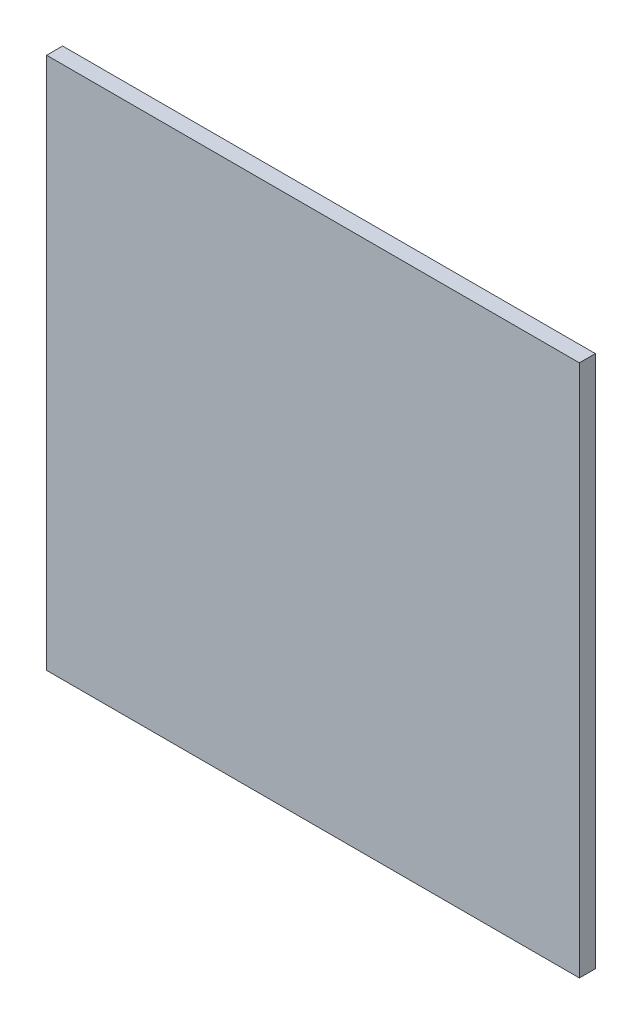
SolidWorks part; units mm, degrees
ref_plane "Front Plane" through (0, 0, 0) normal (0, 0, 1) x (1, 0, 0)
ref_plane "Top Plane" through (0, 0, 0) normal (0, 1, 0) x (1, 0, 0)
ref_plane "Right Plane" through (0, 0, 0) normal (1, 0, 0) x (0, 0, -1)
sketch "Sketch1" plane through (0, 0, 0) normal (0, 0, 1) x (1, 0, 0)
  line L1 (-50, -50) -> (50, -50)
  line L2 (-50, -50) -> (-50, 50)
  line L3 (-50, 50) -> (50, 50)
  line L4 (50, -50) -> (50, 50)
  line L5 (-50, -50) -> (50, 50) construction
  line L6 (-50, 50) -> (50, -50) construction
  point P0 (0, 0)
extrude "Boss-Extrude1" add sketch "Sketch1" along normal blind 3
sketch "Sketch2" plane through (0, 0, 3) normal (0, 0, 1) x (1, 0, 0)
  line L0 (-7.55, -1.32) -> (-5.64, -10.7)
  line L1 (-5.64, -10.7) -> (-5.35, -13.34)
  line L2 (-5.35, -13.34) -> (-5.5, -17.3)
  line L3 (-5.5, -17.3) -> (-6.08, -20.23)
  line L4 (-6.08, -20.23) -> (-6.82, -20.96)
  line L5 (-6.82, -20.96) -> (-9.6, -22.43)
  line L6 (-9.6, -22.43) -> (-9.93, -22.87)
  line L7 (-9.93, -22.87) -> (-9.89, -23.31)
  line L8 (-9.89, -23.31) -> (-9.45, -23.75)
  line L9 (-9.45, -23.75) -> (-5.94, -25.21)
  line L10 (-5.94, -25.21) -> (-5.06, -25.21)
  line L11 (-5.06, -25.21) -> (1.42, -21.87)
  line L12 (1.42, -21.87) -> (1.83, -21.4)
  line L13 (1.83, -21.4) -> (2.13, -13.49)
  line L14 (2.13, -13.49) -> (2.82, -7.33)
  line L15 (2.82, -7.33) -> (3.96, -5.67)
  line L16 (3.96, -5.67) -> (12.68, 0.29)
  line L17 (12.68, 0.29) -> (14.29, 1.76)
  line L18 (14.29, 1.76) -> (14, 2.64)
  line L19 (14, 2.64) -> (13.41, 3.08)
  line L20 (13.41, 3.08) -> (4.32, 6.89)
  line L21 (4.32, 6.89) -> (3, 8.21)
  line L22 (3, 8.21) -> (3, 8.79)
  line L23 (3, 8.79) -> (2.52, 9.28)
  line L24 (3.59, 7.33) -> (3.83, 7.3)
  line L25 (14.44, 5.13) -> (14.44, 6.74)
  line L26 (14.44, 6.74) -> (15.02, 9.82)
  line L27 (15.02, 9.82) -> (15.76, 12.17)
  line L28 (15.76, 12.17) -> (17.22, 15.24)
  line L29 (17.22, 15.24) -> (17.37, 16.42)
  line L30 (17.37, 16.42) -> (13.71, 22.43)
  line L31 (13.71, 22.43) -> (12.83, 23.01)
  line L32 (12.83, 23.01) -> (5.5, 23.45)
  line L33 (5.5, 23.45) -> (-0.07, 23.01)
  line L34 (0.37, 25.07) -> (-0.37, 27.56)
  line L35 (3.59, 28.29) -> (3.3, 28.88)
  line L36 (3.3, 28.88) -> (3.59, 32.69)
  line L37 (3.59, 32.69) -> (4.76, 37.52)
  line L38 (4.76, 37.52) -> (5.79, 38.99)
  line L39 (5.79, 38.99) -> (5.79, 40.75)
  line L40 (5.79, 40.75) -> (-0.22, 45)
  line L41 (-0.22, 45) -> (-1.54, 45)
  line L42 (-1.54, 45) -> (-7.21, 42.32)
  line L43 (-7.21, 42.32) -> (-8.14, 40.6)
  line L44 (-8.14, 40.6) -> (-9.45, 37.23)
  line L45 (-9.45, 37.23) -> (-9.75, 35.77)
  line L46 (-9.75, 35.77) -> (-10.09, 35.42)
  line L47 (-10.09, 35.42) -> (-12.02, 35.45)
  line L48 (-12.02, 35.45) -> (-12.68, 35.03)
  line L49 (-12.68, 35.03) -> (-19.13, 33.71)
  line L50 (-19.13, 33.71) -> (-20.3, 33.71)
  line L51 (-20.3, 33.71) -> (-27.92, 31.37)
  line L52 (-27.92, 31.37) -> (-30.27, 29.46)
  line L53 (-30.27, 29.46) -> (-33.35, 25.72)
  line L54 (-30.86, 25.8) -> (-30.23, 26.08)
  line L55 (-35.18, 22.72) -> (-36.28, 19.5)
  line L56 (-36.28, 19.5) -> (-37.01, 15.54)
  line L57 (-37.01, 15.54) -> (-37.52, 14.76)
  line L58 (-37.52, 14.76) -> (-40.97, 12.17)
  line L59 (-40.97, 12.17) -> (-42.43, 9.09)
  line L60 (-42.43, 9.09) -> (-42.43, 8.21)
  line L61 (-42.43, 8.21) -> (-41.12, 6.89)
  line L62 (-41.12, 6.89) -> (-40.82, 6.89)
  line L63 (-40.82, 6.89) -> (-40.84, 6.34)
  line L64 (-40.84, 6.34) -> (-40.38, 6.3)
  line L65 (-40.38, 6.3) -> (-39.36, 4.98)
  line L66 (-39.36, 4.98) -> (-38.59, 4.57)
  line L67 (-38.59, 4.57) -> (-37.89, 2.64)
  line L68 (-37.89, 2.64) -> (-38.04, 1.32)
  line L69 (-38.04, 1.32) -> (-39.21, -0.15)
  line L70 (-39.21, -0.15) -> (-39.47, -0.91)
  line L71 (-39.47, -0.91) -> (-40.53, -0.88)
  line L72 (-40.53, -0.88) -> (-42, 1.32)
  line L73 (-42, 1.32) -> (-42, 4.84)
  line L74 (-42, 4.84) -> (-39.5, 8.5)
  line L75 (-39.5, 8.5) -> (-38.33, 8.65)
  line L76 (-38.33, 8.65) -> (-36.64, 8.14)
  line L77 (-33.86, 11.8) -> (-32.91, 12.83)
  line L78 (-32.91, 12.83) -> (-31.88, 13.19)
  line L79 (-31.88, 13.19) -> (-24.7, 12.46)
  line L80 (-24.7, 12.46) -> (-24.32, 12.23)
  line L81 (-23.75, 15.39) -> (-24.26, 14.22)
  line L82 (-24.26, 14.22) -> (-24.41, 12.75)
  line L83 (-24.41, 12.75) -> (-23.82, 10.85)
  line L84 (-23.82, 10.85) -> (-22.06, 7.77)
  line L85 (-22.06, 7.77) -> (-22.06, 6.89)
  line L86 (-22.06, 6.89) -> (-22.37, 6.45)
  line L87 (-24.48, 0.07) -> (-19.57, -3.08)
  line L88 (-19.57, -3.08) -> (-17.86, -3.57)
  line L89 (-13.71, -0.44) -> (-12.83, 1.17)
  line L90 (-12.83, 1.17) -> (-12.32, 2.89)
  line L91 (-12.32, 2.89) -> (-12.39, 3.22)
  line L92 (-15.98, 1.32) -> (-17.86, -3.57)
  line L93 (-17.86, -3.57) -> (-17.81, -4.1)
  line L94 (-17.81, -4.1) -> (-16.05, -6.45)
  line L95 (-16.05, -6.45) -> (-12.83, -12.46)
  line L96 (-12.83, -12.46) -> (-12.68, -17.88)
  line L97 (-12.68, -17.88) -> (-12.2, -18.68)
  line L98 (-12.81, -19.71) -> (-14, -19.79)
  line L99 (-14, -19.79) -> (-16.86, -18.98)
  line L100 (-10.03, -19.65) -> (-9.75, -18.76)
  line L101 (-9.75, -18.76) -> (-12.2, -18.68)
  line L102 (-12.2, -18.68) -> (-12.81, -19.71)
  line L103 (-12.81, -19.71) -> (-12.83, -20.37)
  line L104 (-12.83, -20.37) -> (-12.09, -20.96)
  line L105 (-12.09, -20.96) -> (-10.77, -20.67)
  line L106 (-10.77, -20.67) -> (-8.43, -18.03)
  line L107 (-8.43, -18.03) -> (-8.23, -17.27)
  line L108 (-8.23, -17.27) -> (-9.16, -16.42)
  line L109 (-9.16, -16.42) -> (-9.16, -14.66)
  line L110 (-9.16, -14.66) -> (-8.43, -10.26)
  line L111 (-8.43, -10.26) -> (-7.67, -7.73)
  line L112 (-7.67, -7.73) -> (-9.89, -3.96)
  line L113 (-9.89, -3.96) -> (-10.55, -1.47)
  line L114 (-7.67, -7.73) -> (-6.41, -7.62)
  line L115 (2.82, -7.33) -> (3, -7.33)
  line L116 (8.21, -19.79) -> (10.04, -23.16)
  line L117 (10.04, -23.16) -> (10.63, -23.75)
  line L118 (10.63, -23.75) -> (11.13, -23.83)
  line L119 (11.13, -23.83) -> (11.51, -23.45)
  line L120 (11.51, -23.45) -> (12.68, -19.93)
  line L121 (12.68, -19.93) -> (15.17, -15.54)
  line L122 (15.17, -15.54) -> (21.03, -8.21)
  line L123 (21.03, -8.21) -> (25.58, -4.25)
  line L124 (25.58, -4.25) -> (25.87, -3.37)
  line L125 (25.87, -3.37) -> (26.31, 6.01)
  line L126 (26.31, 6.01) -> (26.75, 9.53)
  line L127 (26.75, 9.53) -> (27.78, 14.95)
  line L128 (27.78, 14.95) -> (29.54, 19.2)
  line L129 (29.54, 19.2) -> (31, 20.37)
  line L130 (31, 20.37) -> (32.32, 20.96)
  line L131 (32.32, 20.96) -> (34.52, 20.52)
  line L132 (34.52, 20.52) -> (36.13, 19.79)
  line L133 (36.13, 19.79) -> (37.6, 20.08)
  line L134 (37.6, 20.08) -> (41.12, 18.18)
  line L135 (41.12, 18.18) -> (41.89, 17.15)
  line L136 (41.89, 17.15) -> (41.7, 16.56)
  line L137 (41.7, 16.56) -> (39.5, 14.51)
  line L138 (39.5, 14.51) -> (35.99, 9.82)
  line L139 (35.99, 9.82) -> (34.23, 6.45)
  line L140 (34.23, 6.45) -> (32.76, 1.91)
  line L141 (32.76, 1.91) -> (32.17, -1.47)
  line L142 (32.17, -1.47) -> (32.17, -5.28)
  line L143 (32.17, -5.28) -> (33.05, -8.94)
  line L144 (33.05, -8.94) -> (34.23, -11.58)
  line L145 (34.23, -11.58) -> (34.3, -12.68)
  line L146 (34.3, -12.68) -> (30.56, -15.54)
  line L147 (30.56, -15.54) -> (25.87, -19.79)
  line L148 (25.87, -19.79) -> (21.47, -26.09)
  line L149 (21.47, -26.09) -> (18.98, -31.51)
  line L150 (18.98, -31.51) -> (18.25, -33.57)
  line L151 (18.25, -33.57) -> (17.52, -37.38)
  line L152 (17.52, -37.38) -> (16.78, -38.4)
  line L153 (16.78, -38.4) -> (17.52, -40.16)
  line L154 (16.97, -37.92) -> (15.76, -37.96)
  line L155 (15.76, -37.96) -> (15.17, -37.23)
  line L156 (15.17, -37.23) -> (15.02, -34.74)
  line L157 (15.02, -34.74) -> (14.29, -33.13)
  line L158 (14.29, -33.13) -> (13.49, -30.2)
  line L159 (9.09, -29.9) -> (10.61, -32.53)
  line L160 (10.61, -32.53) -> (13.56, -36.35)
  line L161 (13.56, -36.35) -> (15.05, -36.72)
  line L162 (25.29, -45) -> (25.14, -42.95)
  line L163 (25.14, -42.95) -> (26.02, -36.35)
  line L164 (26.02, -36.35) -> (27.78, -30.64)
  line L165 (27.78, -30.64) -> (29.54, -26.68)
  line L166 (29.54, -26.68) -> (32.17, -22.57)
  line L167 (32.17, -22.57) -> (34.96, -19.2)
  line L168 (34.96, -19.2) -> (38.04, -15.98)
  line L169 (38.04, -15.98) -> (41.7, -13.05)
  line L170 (41.7, -13.05) -> (42.43, -12.17)
  line L171 (42.43, -12.17) -> (42.43, -11.29)
  line L172 (42.43, -11.29) -> (41.41, -9.97)
  line L173 (41.41, -9.97) -> (39.36, -6.01)
  line L174 (39.36, -6.01) -> (38.33, -1.91)
  line L175 (38.33, -1.91) -> (38.33, 1.03)
  line L176 (38.33, 1.03) -> (38.92, 3.81)
  line L177 (38.92, 3.81) -> (39.94, 6.89)
  line L178 (39.94, 6.89) -> (42, 11.14)
  line L179 (31.73, 20.52) -> (31.82, 20.84)
  line L180 (31.82, 20.84) -> (31.88, 21.25)
  line L181 (31.88, 21.25) -> (31.29, 22.13)
  line L182 (31.29, 22.13) -> (24.99, 25.07)
  line L183 (24.99, 25.07) -> (19.57, 27.12)
  line L184 (19.57, 27.12) -> (13.27, 28.66)
  line L185 (9.45, 26.38) -> (7.4, 32.25)
  line L186 (7.4, 32.25) -> (6.23, 37.82)
  line L187 (6.23, 37.82) -> (5.33, 38.15)
  line L188 (5.33, 38.15) -> (4.91, 37.96)
  line L189 (-12.02, 35.45) -> (-12.24, 36.35)
  line L190 (-12.24, 36.35) -> (-18.25, 41.48)
  line L191 (-18.25, 41.48) -> (-19.13, 41.48)
  line L192 (-19.13, 41.48) -> (-21.47, 40.6)
  line L193 (-21.47, 40.6) -> (-22.06, 40.02)
  line L194 (-22.06, 40.02) -> (-21.62, 36.21)
  line L195 (-21.62, 36.21) -> (-20.89, 33.57)
  line L196 (-22.21, 33.01) -> (-22.5, 26.53)
  line L197 (-22.5, 26.53) -> (-22.13, 24.92)
  line L198 (-24.7, 30.12) -> (-28.95, 27.12)
  line L199 (-28.95, 27.12) -> (-31.59, 24.77)
  line L200 (-31.59, 24.77) -> (-33.2, 22.13)
  line L201 (-33.2, 22.13) -> (-34.3, 19.64)
  line L202 (-33.64, 16.34) -> (-35.4, 15.83)
  line L203 (-35.4, 15.83) -> (-36.89, 15.98)
  line L204 (-25.8, 18.54) -> (-18.1, 21.84)
  line L205 (-18.1, 21.84) -> (-14.14, 22.94)
  line L206 (-11.07, 22.13) -> (-6.08, 21.69)
  line L207 (-1.93, 18.41) -> (3, 11.14)
  line L208 (3, 11.14) -> (3.15, 10.11)
  line L209 (3.15, 10.11) -> (2.52, 9.28)
  line L210 (2.52, 9.28) -> (0.66, 8.36)
  line L211 (0.66, 8.36) -> (-8.87, 2.05)
  line L212 (-8.87, 2.05) -> (-12.32, 2.89)
  line L213 (-12.32, 2.89) -> (-12.68, 3.37)
  line L214 (-12.68, 3.37) -> (-20.89, 6.6)
  line L215 (-20.89, 6.6) -> (-22.37, 6.45)
  line L216 (-22.37, 6.45) -> (-27.19, 2.49)
  line L217 (-27.19, 2.49) -> (-27.78, 2.35)
  line L218 (-27.78, 2.35) -> (-29.98, 0.59)
  line L219 (-29.98, 0.59) -> (-31, 1.47)
  line L220 (-31, 1.47) -> (-32.17, 1.47)
  line L221 (-32.17, 1.47) -> (-36.43, 0.59)
  line L222 (-35.25, -1.76) -> (-34.81, -4.1)
  line L223 (-34.81, -4.1) -> (-33.57, -5.41)
  line L224 (-27.61, -3.93) -> (-28.95, -2.2)
  line L225 (-28.95, -2.2) -> (-29.68, 0)
  line L226 (-29.68, 0) -> (-28.97, 1.27)
  line L227 (-28.97, 1.27) -> (-28.8, 1.61)
  line L228 (-28.51, 1.61) -> (-28.97, 1.27)
  line L229 (-27.61, -3.93) -> (-27.34, -4.1)
  line L230 (-40.82, -0.73) -> (-40.94, -0.42)
  line L231 (14.01, 1.3) -> (14.58, 1.47)
  line L232 (14.58, 1.47) -> (15.61, 1.03)
  line L233 (15.61, 1.03) -> (15.76, 0.59)
  line L234 (11.36, -23.75) -> (11.13, -23.83)
